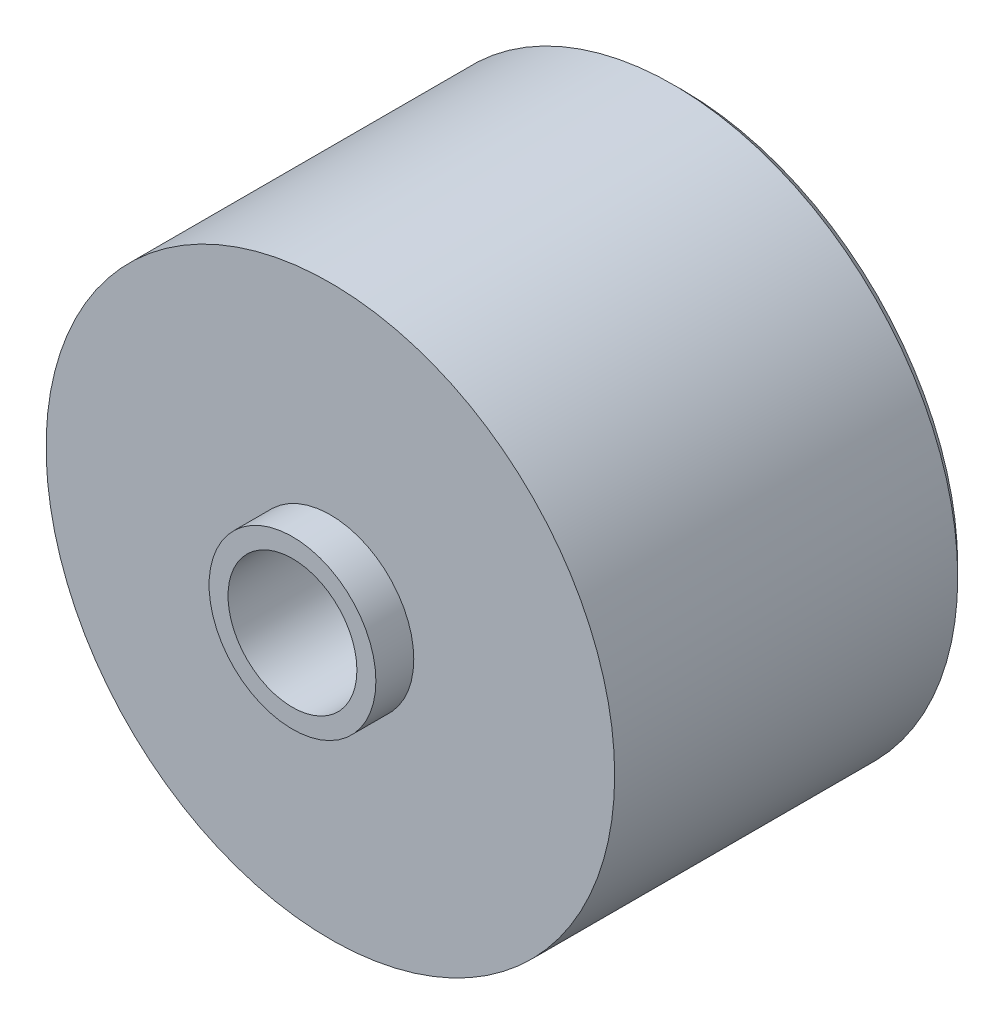
SolidWorks part; units mm, degrees
ref_plane "Front Plane" through (0, 0, 0) normal (0, 0, 1) x (1, 0, 0)
ref_plane "Top Plane" through (0, 0, 0) normal (0, 1, 0) x (1, 0, 0)
ref_plane "Right Plane" through (0, 0, 0) normal (1, 0, 0) x (0, 0, -1)
sketch "Sketch1" plane through (0, 0, 0) normal (0, 0, 1) x (1, 0, 0)
  circle A0 centre (0, 0) radius 1.7
  circle A2 centre (0, 0) radius 7.5
  dimension "D1" = 3.4
  dimension "D2" = 5.8
extrude "Boss-Extrude1" add sketch "Sketch1" along normal blind 9.3
sketch "Sketch2" plane through (0, 0, 9.3) normal (0, 0, 1) x (1, 0, 0)
  circle A0 centre (0, 0) radius 1.7
  circle A2 centre (0, 0) radius 2.2
  dimension "D1" = 3.4
  dimension "D2" = 0.5
extrude "Boss-Extrude2" add sketch "Sketch2" along normal blind 1
chamfer "Chamfer1" distance 0.25 angle 45 2 edges at (1.7, 0, 0) (7.5, 0, 0)
